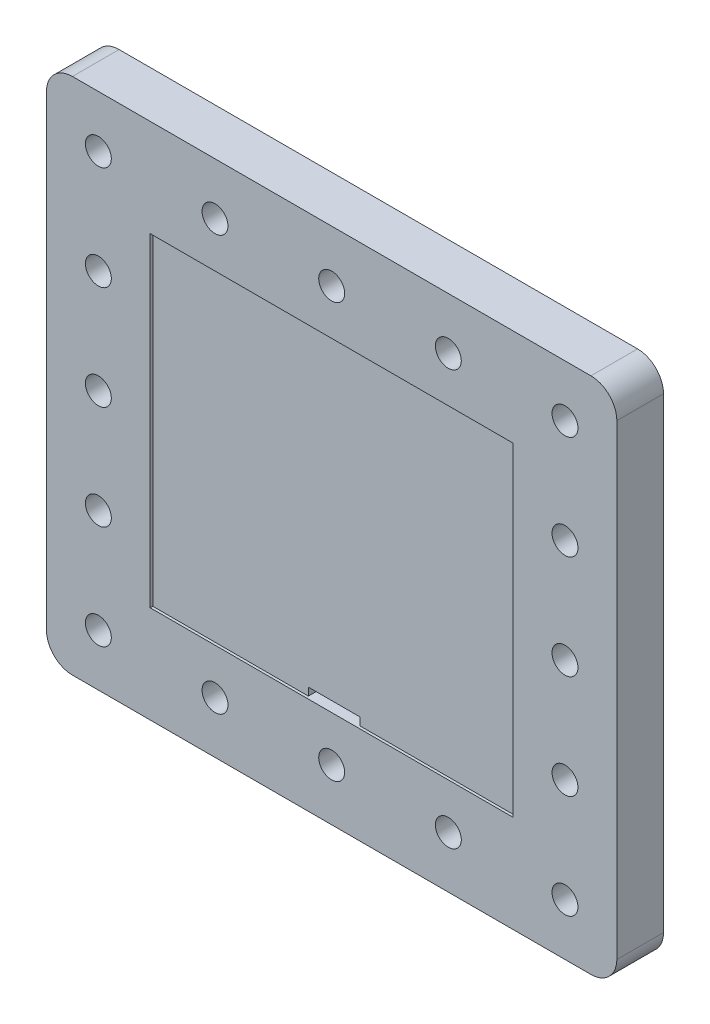
SolidWorks part; units mm, degrees
ref_plane "前视基准面" through (0, 0, 0) normal (0, 0, 1) x (1, 0, 0)
ref_plane "上视基准面" through (0, 0, 0) normal (0, 1, 0) x (1, 0, 0)
ref_plane "右视基准面" through (0, 0, 0) normal (1, 0, 0) x (0, 0, -1)
sketch "草图1" plane through (0, 0, 0) normal (0, 0, 1) x (1, 0, 0)
  line L0 (-90, -80) -> (-90, 80) construction
  line L1 (-100, -100) -> (100, -100)
  line L2 (-110, -90) -> (-110, 90)
  line L3 (-100, 100) -> (100, 100)
  line L4 (110, -90) -> (110, 90)
  line L5 (-110, -100) -> (110, 100) construction
  line L6 (-110, 100) -> (110, -100) construction
  line L7 (90, -80) -> (90, 80) construction
  line L8 (0, 0) -> (0, 49.5511) construction
  line L9 (-90, 80) -> (90, 80) construction
  line L10 (0, 0) -> (38.5286, 0) construction
  arc A0 (100, 100) -> (110, 90) centre (100, 90) cw
  arc A1 (100, -100) -> (110, -90) centre (100, -90) ccw
  arc A2 (-100, -100) -> (-110, -90) centre (-100, -90) cw
  arc A3 (-110, 90) -> (-100, 100) centre (-100, 90) cw
  circle A8 centre (-90, 0) radius 5
  circle A9 centre (90, 0) radius 5
  circle A10 centre (-90, 40) radius 5
  circle A11 centre (-90, -40) radius 5
  circle A12 centre (90, -40) radius 5
  circle A13 centre (90, 40) radius 5
  circle A14 centre (-90, -80) radius 5
  circle A15 centre (-90, 80) radius 5
  circle A16 centre (90, -80) radius 5
  circle A17 centre (90, 80) radius 5
  circle A18 centre (0, 80) radius 5
  circle A19 centre (-45, 80) radius 5
  circle A20 centre (45, 80) radius 5
  circle A21 centre (45, -80) radius 5
  circle A22 centre (0, -80) radius 5
  circle A23 centre (-45, -80) radius 5
  point P0 (0, 0)
  dimension "D2" = 10
  dimension "D3" = 10
  dimension "D4" = 20
  dimension "D5" = 20
  dimension "D6" = 10
  dimension "D8" = 10
  dimension "D9" = 10
  dimension "D10" = 10
  dimension "D11" = 10
  dimension "D12" = 40
  dimension "D13" = 40
  dimension "D16" = 40
  dimension "D17" = 40
  dimension "D18" = 10
  dimension "D19" = 10
  dimension "D20" = 45
  dimension "D21" = 10
  dimension "D22" = 45
  dimension "D1" = 200
  dimension "D7" = 220
  dimension "D14" = 20
  dimension "D15" = 20
extrude "凸台-拉伸1" add sketch "草图1" along normal mid plane 10
sketch "草图3" plane through (0, 0, -5) normal (0, 0, -1) x (-1, 0, 0)
  line L0 (110, 90) -> (110, -90) construction
  line L5 (100, -100) -> (-100, -100) construction
  line L6 (-110, -90) -> (-110, 90) construction
  line L7 (-100, 100) -> (100, 100) construction
  line L8 (110, 90) -> (110, -90)
  line L9 (100, -100) -> (-100, -100)
  line L10 (-110, -90) -> (-110, 90)
  line L11 (-100, 100) -> (100, 100)
  line L13 (-100, -90) -> (100, -90)
  line L14 (-100, -90) -> (-100, 90)
  line L15 (-100, 90) -> (100, 90)
  line L16 (100, -90) -> (100, 90)
  line L17 (-100, -90) -> (100, 90) construction
  line L18 (-100, 90) -> (100, -90) construction
  arc A0 (110, 90) -> (100, 100) centre (100, 90) ccw construction
  arc A1 (100, -100) -> (110, -90) centre (100, -90) ccw construction
  arc A2 (-110, -90) -> (-100, -100) centre (-100, -90) ccw construction
  arc A3 (-100, 100) -> (-110, 90) centre (-100, 90) ccw construction
  arc A4 (110, 90) -> (100, 100) centre (100, 90) ccw
  arc A5 (100, -100) -> (110, -90) centre (100, -90) ccw
  arc A6 (-110, -90) -> (-100, -100) centre (-100, -90) ccw
  arc A7 (-100, 100) -> (-110, 90) centre (-100, 90) ccw
  point P3 (0, 0)
extrude "凸台-拉伸2" add sketch "草图3" along normal blind 8
sketch "草图4" plane through (0, 0, 5) normal (0, 0, 1) x (1, 0, 0)
  line L1 (-70, -62.5) -> (70, -62.5)
  line L2 (-70, -62.5) -> (-70, 62.5)
  line L3 (-70, 62.5) -> (70, 62.5)
  line L4 (70, -62.5) -> (70, 62.5)
  line L5 (-70, -62.5) -> (70, 62.5) construction
  line L6 (-70, 62.5) -> (70, -62.5) construction
  point P0 (0, 0)
  dimension "D1" = 125
  dimension "D2" = 140
extrude "切除-拉伸1" cut sketch "草图4" against normal blind 1
sketch "草图5" plane through (0, 0, 4) normal (0, 0, 1) x (1, 0, 0)
  line L0 (0, -62.5) -> (0, -51.5457) construction
  line L1 (-70, -62.5) -> (70, -62.5) construction
  line L2 (0, -62.5) -> (10, -62.5)
  line L3 (10, -62.5) -> (10, -59.5)
  line L4 (10, -59.5) -> (-10, -59.5)
  line L5 (-10, -62.5) -> (-10, -59.5)
  line L6 (0, -62.5) -> (-10, -62.5)
  point P10 (0, -59.5)
  dimension "D1" = 10
  dimension "D2" = 3
extrude "切除-拉伸2" cut sketch "草图5" against normal through all both and the other way through all
sketch "草图6" plane through (0, -100, 0) normal (0, -1, 0) x (1, 0, 0)
  line L0 (0, 0) -> (0, -13) construction
  line L1 (100, -13) -> (-100, -13) construction
  line L2 (-10, -13) -> (10, -13)
  line L3 (10, -13) -> (10, -10)
  line L4 (10, -10) -> (-10, -10)
  line L5 (-10, -13) -> (-10, -10)
  point P10 (0, -10)
  dimension "D1" = 10
  dimension "D2" = 3
extrude "切除-拉伸3" cut sketch "草图6" against normal blind 5
